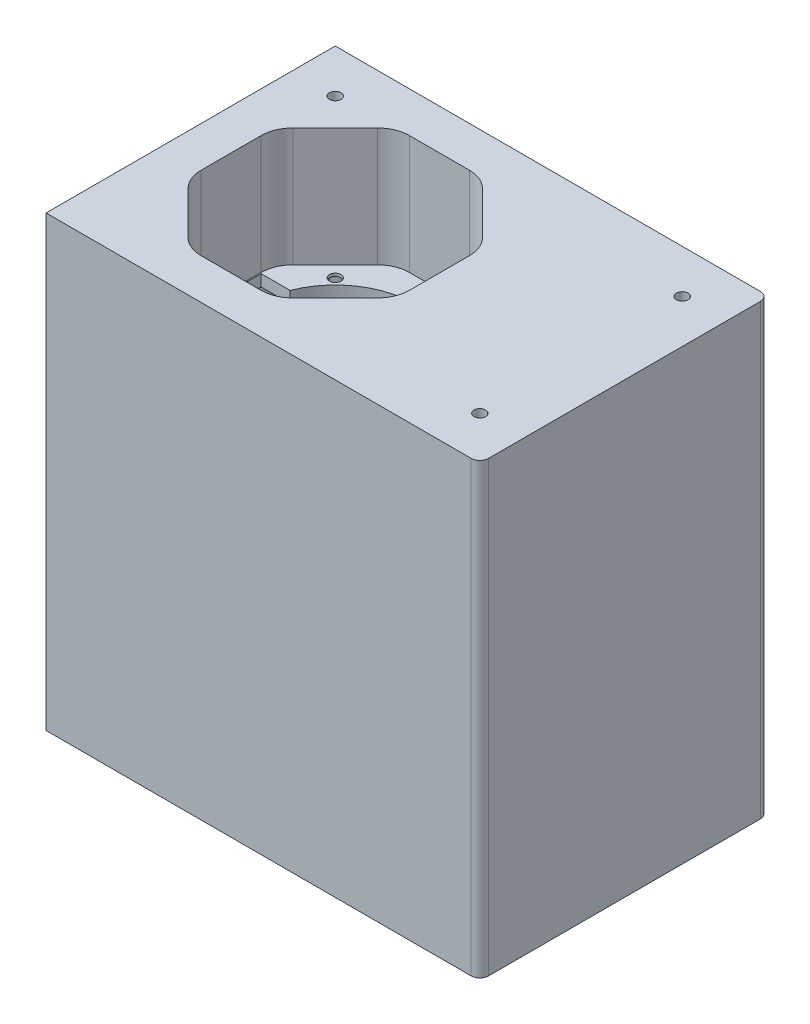
SolidWorks part; units mm, degrees
ref_plane "Front Plane" through (0, 0, 0) normal (0, 0, 1) x (1, 0, 0)
ref_plane "Top Plane" through (0, 0, 0) normal (0, 1, 0) x (1, 0, 0)
ref_plane "Right Plane" through (0, 0, 0) normal (1, 0, 0) x (0, 0, -1)
sketch "Sketch1" plane through (0, 0, 0) normal (0, 1, 0) x (1, 0, 0)
  line L0 (0, 0) -> (-133401.8874, 0) construction
  line L1 (0, 0) -> (0, -133401.8874) construction
  line L3 (-75, 50) -> (75, 50)
  line L4 (-75, 50) -> (-75, -50)
  line L5 (-75, -50) -> (75, -50)
  line L6 (75, 50) -> (75, -50)
  line L7 (-75, 50) -> (75, -50) construction
  line L8 (-75, -50) -> (75, 50) construction
  point P5 (0, 0)
  dimension "D1" = 100
  dimension "D2" = 150
extrude "Boss-Extrude1" add sketch "Sketch1" along normal blind 45
sketch "Sketch2" plane through (0, 45, 0) normal (0, 1, 0) x (1, 0, 0)
  line L0 (0, 0) -> (-50000, 0) construction
  line L1 (0, 0) -> (0, -50000) construction
  line L18 (-25, 0) -> (-25, -50000) construction
  line L19 (75, -50) -> (75, 50) construction
  line L20 (-14.6447, 35) -> (-35.3553, 35) construction
  line L21 (-42.4264, 32.0711) -> (-57.0711, 17.4264) construction
  line L22 (-60, 10.3553) -> (-60, -10.3553) construction
  line L23 (10, 10.3553) -> (10, -10.3553) construction
  line L24 (-7.5736, 32.0711) -> (7.0711, 17.4264) construction
  line L25 (-7.5736, -32.0711) -> (7.0711, -17.4264) construction
  line L26 (-42.4264, -32.0711) -> (-57.0711, -17.4264) construction
  line L27 (-14.6447, -35) -> (-35.3553, -35) construction
  line L28 (-6.8665, -32.7782) -> (7.7782, -18.1335)
  line L29 (11, 10.3553) -> (11, -10.3553)
  line L30 (-6.8665, 32.7782) -> (7.7782, 18.1335)
  line L31 (-14.6447, 36) -> (-35.3553, 36)
  line L32 (-43.1335, 32.7782) -> (-57.7782, 18.1335)
  line L33 (-61, 10.3553) -> (-61, -10.3553)
  line L34 (-43.1335, -32.7782) -> (-57.7782, -18.1335)
  line L35 (-14.6447, -36) -> (-35.3553, -36)
  circle A17 centre (-25, 0) radius 35 construction
  arc A18 (-57.0711, 17.4264) -> (-60, 10.3553) centre (-50, 10.3553) ccw construction
  arc A19 (-57.0711, -17.4264) -> (-60, -10.3553) centre (-50, -10.3553) cw construction
  arc A20 (-42.4264, -32.0711) -> (-35.3553, -35) centre (-35.3553, -25) ccw construction
  arc A21 (-7.5736, -32.0711) -> (-14.6447, -35) centre (-14.6447, -25) cw construction
  arc A22 (7.0711, -17.4264) -> (10, -10.3553) centre (0, -10.3553) ccw construction
  arc A23 (10, 10.3553) -> (7.0711, 17.4264) centre (0, 10.3553) ccw construction
  arc A24 (-7.5736, 32.0711) -> (-14.6447, 35) centre (-14.6447, 25) ccw construction
  arc A25 (-35.3553, 35) -> (-42.4264, 32.0711) centre (-35.3553, 25) ccw construction
  arc A26 (7.7782, -18.1335) -> (11, -10.3553) centre (0, -10.3553) ccw
  arc A27 (11, 10.3553) -> (7.7782, 18.1335) centre (0, 10.3553) ccw
  arc A28 (-6.8665, 32.7782) -> (-14.6447, 36) centre (-14.6447, 25) ccw
  arc A29 (-35.3553, 36) -> (-43.1335, 32.7782) centre (-35.3553, 25) ccw
  arc A30 (-57.7782, 18.1335) -> (-61, 10.3553) centre (-50, 10.3553) ccw
  arc A31 (-57.7782, -18.1335) -> (-61, -10.3553) centre (-50, -10.3553) cw
  arc A32 (-43.1335, -32.7782) -> (-35.3553, -36) centre (-35.3553, -25) ccw
  arc A33 (-6.8665, -32.7782) -> (-14.6447, -36) centre (-14.6447, -25) cw
  point P11 (-25, -35)
  point P18 (-25, 35)
  point P21 (10, 0)
  point P22 (-60, 0)
  point P25 (-60, 14.4975)
  point P28 (-60, -14.4975)
  point P31 (-39.4975, -35)
  point P34 (-10.5025, -35)
  point P37 (10, -14.4975)
  point P40 (10, 14.4975)
  point P43 (-10.5025, 35)
  point P46 (-39.4975, 35)
  dimension "D1" = 100
  dimension "D2" = 70
  dimension "D3" = 10
  dimension "D4" = 1
extrude "Cut-Extrude1" cut sketch "Sketch2" against normal blind 41
sketch "Sketch3" plane through (0, 45, 0) normal (0, 1, 0) x (1, 0, 0)
  line L0 (0, 0) -> (-50000, 0) construction
  line L1 (0, 0) -> (0, -50000) construction
  line L5 (-25, 36) -> (-25, -49964) construction
  line L6 (-14.6447, 36) -> (-35.3553, 36) construction
  line L13 (-50.6174, 10) -> (-60.6174, 10)
  line L14 (-60.6174, 10) -> (-60.6174, -10)
  line L15 (-50.6174, -10) -> (-60.6174, -10)
  arc A2 (-13.1686, 24.8247) -> (-50.6174, 10) centre (-25, 0) ccw
  arc A3 (-50.6174, -10) -> (-13.1686, -24.8247) centre (-25, 0) ccw
  arc A4 (-13.1686, 24.8247) -> (-13.1686, -24.8247) centre (-25, 0) cw
  point P10 (-25, 36)
  point P17 (-60.6174, 0)
  dimension "D1" = 55
  dimension "D2" = 10
  dimension "D3" = 10
extrude "Cut-Extrude2" cut sketch "Sketch3" against normal through all
sketch "Sketch4" plane through (0, 0, 0) normal (0, -1, 0) x (1, 0, 0)
  line L0 (0, 0) -> (-50000, 0) construction
  line L1 (0, 0) -> (0, -50000) construction
  line L2 (-25, 0) -> (-25, -50000) construction
  line L27 (-25, 0) -> (35330.3391, -35355.3391) construction
  line L52 (-0.366, 22.3886) -> (-2.6114, 24.634)
  line L78 (-47.3886, 24.634) -> (-49.634, 22.3886)
  line L79 (-49.634, 22.3886) -> (-48.8121, 19.3214)
  line L80 (-48.8121, 19.3214) -> (-45.7449, 18.4995)
  line L81 (-45.7449, 18.4995) -> (-43.4995, 20.7449)
  line L82 (-43.4995, 20.7449) -> (-44.3214, 23.8121)
  line L83 (-44.3214, 23.8121) -> (-47.3886, 24.634)
  line L84 (-2.6114, 24.634) -> (-5.6786, 23.8121)
  line L85 (-5.6786, 23.8121) -> (-6.5005, 20.7449)
  line L86 (-6.5005, 20.7449) -> (-4.2551, 18.4995)
  line L87 (-4.2551, 18.4995) -> (-1.1879, 19.3214)
  line L88 (-1.1879, 19.3214) -> (-0.366, 22.3886)
  line L89 (-2.6114, -24.634) -> (-0.366, -22.3886)
  line L90 (-0.366, -22.3886) -> (-1.1879, -19.3214)
  line L91 (-1.1879, -19.3214) -> (-4.2551, -18.4995)
  line L92 (-4.2551, -18.4995) -> (-6.5005, -20.7449)
  line L93 (-6.5005, -20.7449) -> (-5.6786, -23.8121)
  line L94 (-5.6786, -23.8121) -> (-2.6114, -24.634)
  line L95 (-49.634, -22.3886) -> (-47.3886, -24.634)
  line L96 (-47.3886, -24.634) -> (-44.3214, -23.8121)
  line L97 (-44.3214, -23.8121) -> (-43.4995, -20.7449)
  line L98 (-43.4995, -20.7449) -> (-45.7449, -18.4995)
  line L99 (-45.7449, -18.4995) -> (-48.8121, -19.3214)
  line L100 (-48.8121, -19.3214) -> (-49.634, -22.3886)
  circle A3 centre (-25, 0) radius 30.5 construction
  circle A4 centre (-46.5668, 21.5668) radius 2.75 construction
  point P40 (-25, 0)
  dimension "D1" = 45
  dimension "D3" = 5.5
  dimension "D2" = 61
  dimension "D4" = 4
extrude "Cut-Extrude3" cut sketch "Sketch4" against normal blind 3 contours L79 L80 L81 L82 L83 L78 | L52 L84 L85 L86 L87 L88 | L89 L90 L91 L92 L93 L94 | L95 L96 L97 L98 L99 L100
sketch "Sketch5" plane through (0, 4, 0) normal (0, 1, 0) x (1, 0, 0)
  line L0 (0, 0) -> (-50000, 0) construction
  line L1 (0, 0) -> (0, -50000) construction
  line L2 (-25, 0) -> (-25, -50000) construction
  line L3 (-25, 0) -> (35330.3391, -35355.3391) construction
  circle A10 centre (-25, 0) radius 30.5 construction
  circle A11 centre (-46.5668, 21.5668) radius 2
  circle A12 centre (-3.4332, 21.5668) radius 2
  circle A13 centre (-3.4332, -21.5668) radius 2
  circle A14 centre (-46.5668, -21.5668) radius 2
  point P23 (-25, 0)
  dimension "D1" = 45
  dimension "D3" = 4
  dimension "D2" = 61
extrude "Cut-Extrude4" cut sketch "Sketch5" against normal through all
sketch "Sketch6" plane through (0, 0, 0) normal (0, -1, 0) x (1, 0, 0)
  line L0 (0, 0) -> (-50000, 0) construction
  line L1 (0, 0) -> (0, -50000) construction
  line L2 (65, -40) -> (65, 40)
  line L3 (65, 40) -> (-65, 40)
  line L4 (-65, 40) -> (-65, -40)
  line L5 (-65, -40) -> (65, -40)
  line L6 (75, -50) -> (75, 50)
  line L7 (75, 50) -> (-75, 50)
  line L8 (-75, 50) -> (-75, -50)
  line L9 (-75, -50) -> (75, -50)
  line L10 (75, -50) -> (75, 50)
  line L11 (75, 50) -> (-75, 50)
  line L12 (-75, 50) -> (-75, -50)
  line L13 (-75, -50) -> (75, -50)
  dimension "D1" = 0
  dimension "D2" = 10
extrude "Boss-Extrude2" add sketch "Sketch6" along normal blind 110
sketch "Sketch7" plane through (0, -110, 0) normal (0, -1, 0) x (1, 0, 0)
  line L0 (0, 0) -> (-50000, 0) construction
  line L1 (0, 0) -> (0, -50000) construction
  line L2 (75, 50) -> (-75, 50) construction
  line L3 (75, -50) -> (75, 50) construction
  line L4 (-75, -50) -> (75, -50) construction
  line L5 (-75, 50) -> (-75, -50) construction
  circle A1 centre (70, 45) radius 2
  circle A2 centre (70, -45) radius 2
  circle A4 centre (-70, -30) radius 2
  circle A5 centre (-70, 12) radius 2
  dimension "D1" = 4
  dimension "D2" = 5
  dimension "D3" = 5
  dimension "D4" = 4
  dimension "D5" = 20
  dimension "D6" = 5
  dimension "D7" = 4
  dimension "D8" = 5
  dimension "D9" = 42
extrude "Cut-Extrude5" cut sketch "Sketch7" against normal blind 15
sketch "Sketch11" plane through (-75, 0, 0) normal (1, 0, 0) x (0, 0, -1)
  line L0 (0, 0) -> (0, -50000) construction
  line L1 (0, 0) -> (-50000, 0) construction
  line L3 (0, -32.5) -> (-50000, -32.5) construction
  line L4 (50, -110) -> (-50, -110) construction
  line L17 (-30, 17.5) -> (30, 17.5)
  line L18 (-30, 17.5) -> (-30, -82.5)
  line L19 (-30, -82.5) -> (30, -82.5)
  line L20 (30, 17.5) -> (30, -82.5)
  line L21 (-30, 17.5) -> (30, -82.5) construction
  line L22 (-30, -82.5) -> (30, 17.5) construction
  point P9 (0, -32.5)
  dimension "D1" = 77.5
  dimension "D2" = 100
  dimension "D3" = 60
extrude "Boss-Extrude5" add sketch "Sketch11" against normal blind 20
sketch "Sketch12" plane through (0, 0, -30) normal (0, 0, -1) x (-1, 0, 0)
  line L0 (0, 0) -> (50000, 0) construction
  line L1 (85, 27.5) -> (85, -49972.5) construction
  line L2 (95, 17.5) -> (75, 17.5) construction
  line L3 (95, -32.5) -> (-49905, -32.5) construction
  line L4 (95, -82.5) -> (95, 17.5) construction
  circle A0 centre (85, 0) radius 2
  circle A1 centre (85, -65) radius 2
  point P7 (85, 17.5)
  point P12 (95, -32.5)
  dimension "D1" = 4
extrude "Cut-Extrude6" cut sketch "Sketch12" against normal blind 15
mirror "Mirror1" about plane through (0, 0, 0) normal (0, 0, 1) of "Cut-Extrude6"
sketch "Sketch13" plane through (0, -82.5, 0) normal (0, -1, 0) x (1, 0, 0)
  line L0 (0, 0) -> (-50000, 0) construction
  line L1 (-85, 30) -> (-85, -49970) construction
  line L2 (-95, 30) -> (-75, 30) construction
  circle A0 centre (-85, 15) radius 2
  circle A1 centre (-85, -15) radius 2
  point P7 (-85, 30)
  dimension "D1" = 4
  dimension "D2" = 15
extrude "Cut-Extrude7" cut sketch "Sketch13" against normal blind 15
sketch "Sketch14" plane through (0, 45, 0) normal (0, 1, 0) x (1, 0, 0)
  line L0 (0, 0) -> (-50000, 0) construction
  line L1 (0, 0) -> (0, -50000) construction
  line L2 (45, -20) -> (45, 20) construction
  line L3 (45, 20) -> (-45, 20) construction
  line L4 (-45, 20) -> (-45, -20) construction
  line L5 (-45, -20) -> (45, -20) construction
  line L6 (75, -50) -> (75, 50)
  line L7 (75, 50) -> (-75, 50)
  line L8 (-75, 50) -> (-75, -50)
  line L9 (-75, -50) -> (75, -50)
  line L10 (75, -50) -> (75, 50) construction
  line L11 (75, 50) -> (-75, 50) construction
  line L12 (-75, 50) -> (-75, -50) construction
  line L13 (-75, -50) -> (75, -50) construction
  line L14 (45, 20) -> (75, 50) construction
  circle A0 centre (60, 35) radius 2
  circle A1 centre (60, -35) radius 2
  circle A2 centre (-60, 35) radius 2
  dimension "D3" = 4
  dimension "D1" = 0
  dimension "D2" = 30
extrude "Cut-Extrude8" cut sketch "Sketch14" against normal blind 15
sketch "Sketch15" plane through (0, 0, 0) normal (0, -1, 0) x (1, 0, 0)
  line L0 (0, 0) -> (-50000, 0) construction
  line L1 (0, 0) -> (0, -50000) construction
  line L3 (15, -40) -> (65, -40)
  line L4 (15, -40) -> (15, 40)
  line L5 (15, 40) -> (65, 40)
  line L6 (65, -40) -> (65, 40)
  line L7 (15, -40) -> (65, 40) construction
  line L8 (15, 40) -> (65, -40) construction
  point P5 (40, 0)
  dimension "D1" = 50
extrude "Boss-Extrude6" add sketch "Sketch15" along normal up to surface (110 mm away) up to face at (70, -110, 47)
fillet "Fillet1" radius 3 10 edges at (-95, 17.5, 0) (-95, -32.5, 30) (-95, -82.5, 0) (-95, -32.5, -30) (-85, -82.5, -30) (-85, -82.5, 30) (-85, 17.5, 30) (-85, 17.5, -30) (75, -32.5, -50) (75, -32.5, 50)
